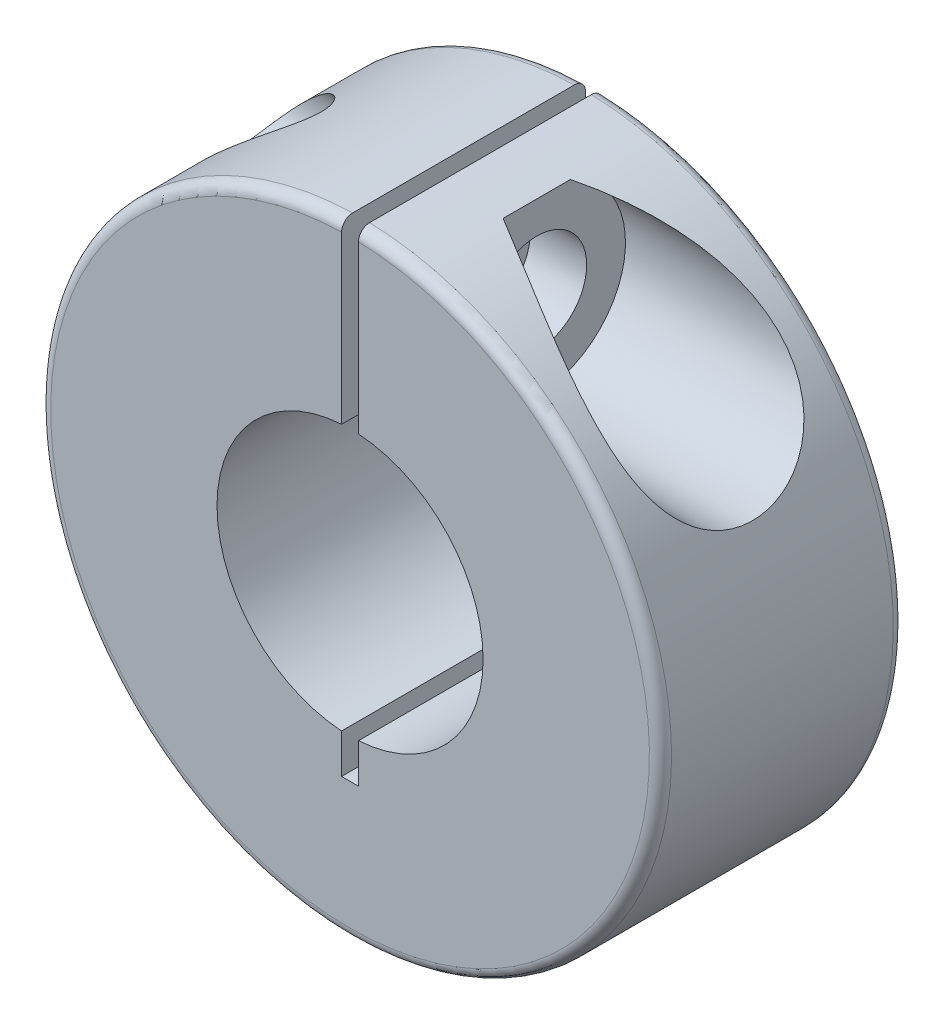
SolidWorks part; units mm, degrees
ref_plane "Front Plane" through (0, 0, 0) normal (0, 0, 1) x (1, 0, 0)
ref_plane "Top Plane" through (0, 0, 0) normal (0, 1, 0) x (1, 0, 0)
ref_plane "Right Plane" through (0, 0, 0) normal (1, 0, 0) x (0, 0, -1)
sketch "Sketch1" plane through (0, 0, 0) normal (0, 0, 1) x (1, 0, 0)
  line L0 (5.1962, 3) -> (5.1962, -3)
  line L1 (-0.381, -7.7659) -> (-0.381, -5.9879)
  line L2 (0, -6) -> (0, -7.0924) construction
  line L3 (0.381, -7.7659) -> (0.381, -5.9879)
  line L4 (-0.381, -7.7659) -> (0.381, -7.7659)
  line L5 (0, 6) -> (0, 14) construction
  line L6 (-0.381, 13.9948) -> (-0.381, 5.9879)
  line L7 (0.381, 13.9948) -> (0.381, 5.9879)
  circle A0 centre (0, 0) radius 6
  circle A1 centre (0, 0) radius 14
  dimension "D1" = 28
  dimension "D2" = 12
  dimension "D3" = 6
  dimension "D4" = 0.762
  dimension "D5" = 1.778
  dimension "D6" = 0.381
extrude "Boss-Extrude1" add sketch "Sketch1" along normal blind 11 contours L6 A1 L7 A0 L3 L4 L1
sketch "Sketch4" plane through (0.381, 0, 0) normal (-1, 0, 0) x (0, 0, 1)
  line L0 (0, 9.9914) -> (11, 9.9914) construction
  line L1 (0, 13.9948) -> (0, 5.9879) construction
  line L2 (11, 13.9948) -> (11, 5.9879) construction
  point P6 (5.5, 9.9914)
ref_plane "Plane4" through (0, 9.9914, 0) normal (0, -1, 0) x (0, 0, 1)
sketch "Sketch7" plane through (0, 9.9914, 0) normal (0, -1, 0) x (0, 0, 1)
  line L0 (5.5, -0.381) -> (5.5, -14)
  dimension "D1" = 13.619
ref_plane "Plane5" through (14, 0, 0) normal (-1, 0, 0) x (0, 0, 1)
hole_wizard "CBORE for M4 SHCS2" positions "Sketch19" profile "Sketch20" counterbore size "M4" standard "ANSI Metric" end condition through all
sketch "Sketch19" plane through (14, 0, 0) normal (-1, 0, 0) x (0, 0, 1)
  point P0 (5.5, 9.9914)
sketch "Sketch20" plane through (14, 9.9914, 5.5) normal (0, 1, 0) x (0, 0, -1)
  line L0 (0, 0) -> (0, 28)
  line L1 (0, 28) -> (2.25, 28)
  line L3 (2.25, 28) -> (2.25, 11.079)
  line L4 (2.25, 11.079) -> (4, 11.079)
  line L5 (4, 11.079) -> (4, 0)
  line L7 (4, 0) -> (0, 0)
  line L11 (0, -6.35) -> (0, 107.95) construction
  dimension "Thru Hole Dia." = 4.5
  dimension "Thru Hole Depth" = 28
  dimension "C'Bore Dia." = 8
  dimension "C'Bore Depth" = 11.079
fillet "Fillet1" radius 0.5 2 edges at (0, -14, 0) (0, -14, 11)
